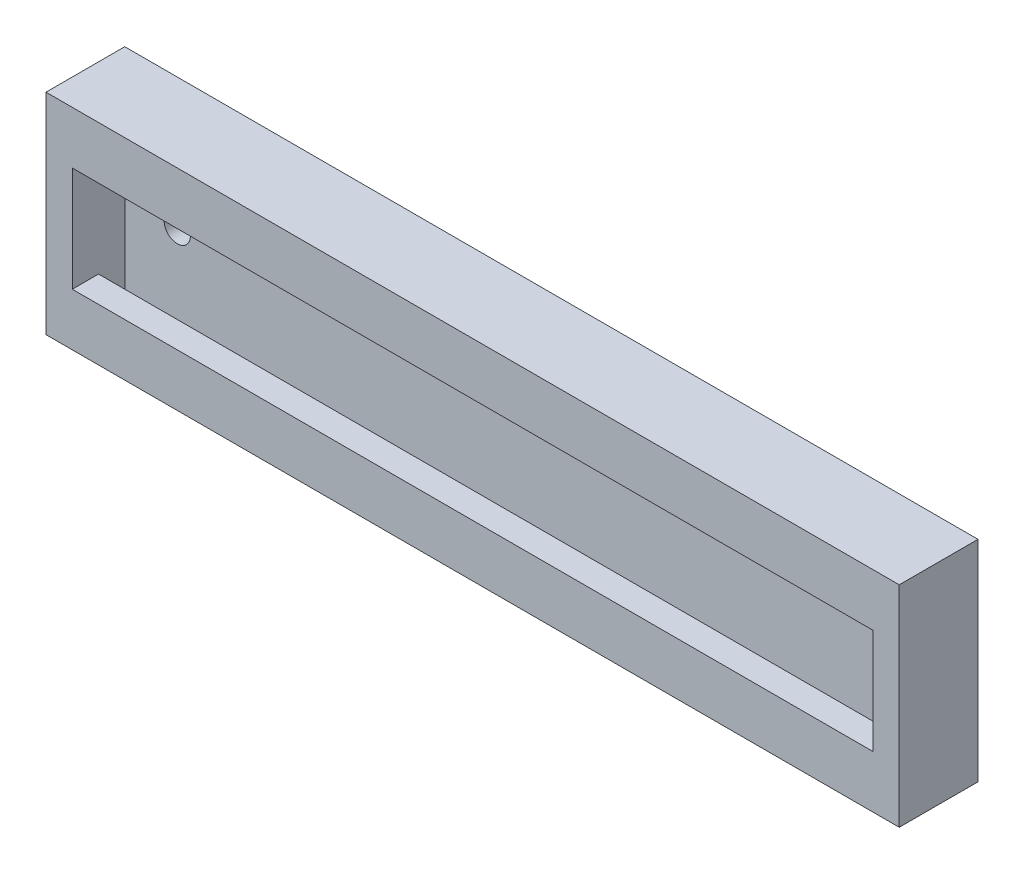
SolidWorks part; units mm, degrees
ref_plane "Front Plane" through (0, 0, 0) normal (0, 0, 1) x (1, 0, 0)
ref_plane "Top Plane" through (0, 0, 0) normal (0, 1, 0) x (1, 0, 0)
ref_plane "Right Plane" through (0, 0, 0) normal (1, 0, 0) x (0, 0, -1)
sketch "Sketch1" plane through (0, 0, 0) normal (0, 0, 1) x (1, 0, 0)
  line L1 (-32.5, -8) -> (32.5, -8)
  line L2 (-32.5, -8) -> (-32.5, 8)
  line L3 (-32.5, 8) -> (32.5, 8)
  line L4 (32.5, -8) -> (32.5, 8)
  line L5 (-32.5, -8) -> (32.5, 8) construction
  line L6 (-32.5, 8) -> (32.5, -8) construction
  point P0 (0, 0)
  dimension "D1" = 65
  dimension "D2" = 16
extrude "Boss-Extrude1" add sketch "Sketch1" along normal blind 2
sketch "Sketch2" plane through (0, 0, 2) normal (0, 0, 1) x (1, 0, 0)
  line L1 (-32.5, 8) -> (32.5, 8)
  line L2 (-32.5, 8) -> (-32.5, -8)
  line L3 (-32.5, -8) -> (32.5, -8)
  line L4 (32.5, 8) -> (32.5, -8)
  line L5 (-32.5, 8) -> (32.5, -8) construction
  line L6 (-32.5, -8) -> (32.5, 8) construction
  line L7 (-30.5, 6) -> (30.5, 6)
  line L8 (-30.5, 6) -> (-30.5, -6)
  line L9 (-30.5, -6) -> (30.5, -6)
  line L10 (30.5, 6) -> (30.5, -6)
  line L11 (-30.5, 6) -> (30.5, -6) construction
  line L12 (-30.5, -6) -> (30.5, 6) construction
  point P0 (0, 0)
  point P7 (0, 0)
  dimension "D1" = 2
  dimension "D2" = 2
extrude "Boss-Extrude2" add sketch "Sketch2" along normal blind 2
sketch "Sketch4" plane through (0, 0, 4) normal (0, 0, 1) x (1, 0, 0)
  line L0 (30.5, -6) -> (30.5, 6) construction
  line L1 (-32.5, 8) -> (32.5, 8)
  line L2 (-32.5, 8) -> (-32.5, -8)
  line L3 (-32.5, -8) -> (32.5, -8)
  line L4 (32.5, 8) -> (32.5, -8)
  line L5 (-32.5, 8) -> (32.5, -8) construction
  line L6 (-32.5, -8) -> (32.5, 8) construction
  line L7 (-30.5, 4) -> (30.5, 4)
  line L8 (-30.5, 4) -> (-30.5, -4)
  line L9 (-30.5, -4) -> (30.5, -4)
  line L10 (30.5, 4) -> (30.5, -4)
  line L11 (-30.5, 4) -> (30.5, -4) construction
  line L12 (-30.5, -4) -> (30.5, 4) construction
  line L13 (30.5, 6) -> (-30.5, 6) construction
  point P0 (0, 0)
  point P7 (0, 0)
  dimension "D1" = 2
extrude "Boss-Extrude3" add sketch "Sketch4" along normal blind 2
sketch "Sketch5" plane through (0, 0, 2) normal (0, 0, 1) x (1, 0, 0)
  line L0 (-32.5, 8) -> (-32.5, -8) construction
  line L1 (32.5, 8) -> (-32.5, 8) construction
  circle A0 centre (-26.5, 0) radius 1
  dimension "D1" = 2
  dimension "D2" = 6
  dimension "D3" = 8
extrude "Cut-Extrude1" cut sketch "Sketch5" against normal blind 1
